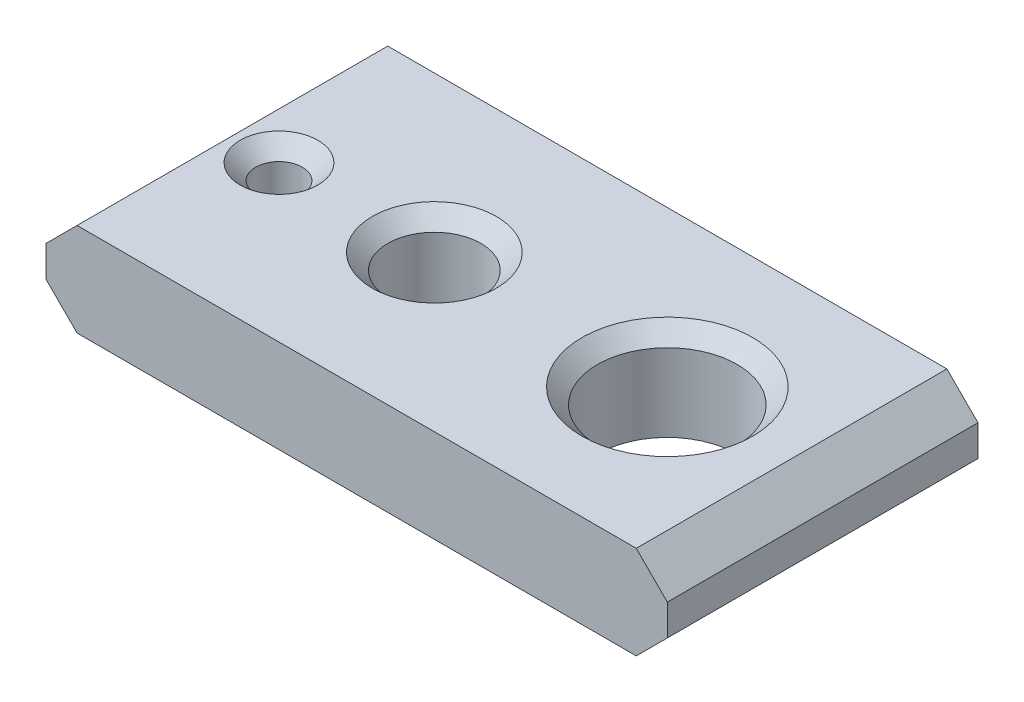
SolidWorks part; units mm, degrees
ref_plane "Alzado" through (0, 0, 0) normal (0, 0, 1) x (1, 0, 0)
ref_plane "Planta" through (0, 0, 0) normal (0, 1, 0) x (1, 0, 0)
ref_plane "Vista lateral" through (0, 0, 0) normal (1, 0, 0) x (0, 0, -1)
sketch "Croquis2" plane through (0, 0, 0) normal (0, 0, 1) x (1, 0, 0)
  line L3 (10, 30) -> (190, 30)
  line L7 (190, 0) -> (10, 0)
  line L8 (0, 10) -> (0, 20)
  line L9 (200, 10) -> (200, 20)
  line L10 (190, 30) -> (200, 20)
  line L11 (200, 10) -> (190, 0)
  line L12 (0, 20) -> (10, 30)
  line L13 (10, 0) -> (0, 10)
  point P0 (0, 0)
  point P5 (0, 30)
  point P6 (200, 30)
  point P9 (200, 0)
  dimension "D1" = 200
  dimension "D2" = 30
extrude "Saliente-Extruir1" add sketch "Croquis2" against normal blind 100
sketch "Croquis3" plane through (0, 30, 0) normal (0, 1, 0) x (1, 0, 0)
  line L0 (0, 100) -> (0, 0) construction
  circle A0 centre (25, 50) radius 7.5
  circle A1 centre (75, 50) radius 15
  circle A2 centre (150, 50) radius 22.5
  point P6 (0, 0)
  point P7 (30.2717, 50)
  point P8 (67.7507, 50)
  point P9 (71.2371, 50)
  point P10 (140.0938, 50)
  dimension "D4" = 15
  dimension "D5" = 30
  dimension "D6" = 45
  dimension "D1" = 25
  dimension "D2" = 50
  dimension "D3" = 75
  dimension "D7" = 50
extrude "Cortar-Extruir1" cut sketch "Croquis3" against normal through all
chamfer "Chaflán1" distance 5 angle 45 3 edges at (150, 30, -27.5) (25, 30, -42.5) (75, 30, -35)
